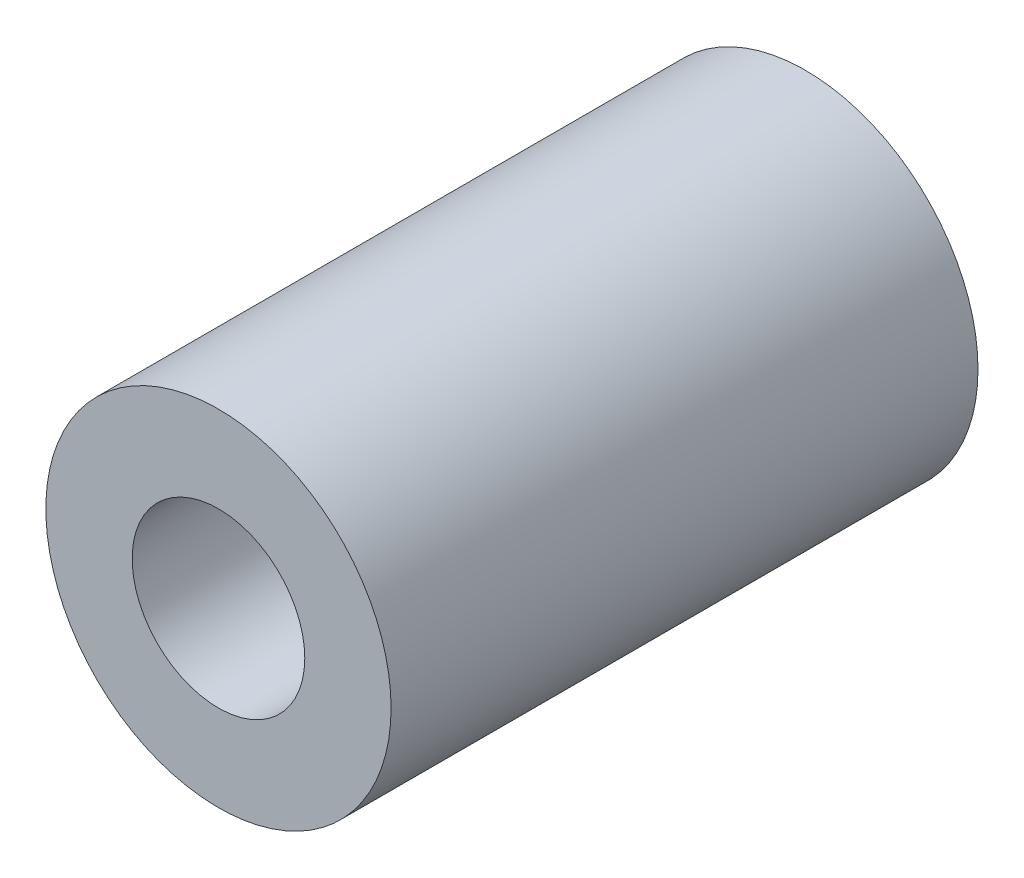
SolidWorks part; units mm, degrees
ref_plane "前视基准面" through (0, 0, 0) normal (0, 0, 1) x (1, 0, 0)
ref_plane "上视基准面" through (0, 0, 0) normal (0, 1, 0) x (1, 0, 0)
ref_plane "右视基准面" through (0, 0, 0) normal (1, 0, 0) x (0, 0, -1)
other "Configuration Table"
sketch "草图8" plane through (0, 0, 0) normal (0, 0, 1) x (1, 0, 0)
  circle A0 centre (0, 0) radius 50
  circle A1 centre (0, 0) radius 25
extrude "凸台-拉伸1" add sketch "草图8" along normal blind 170
